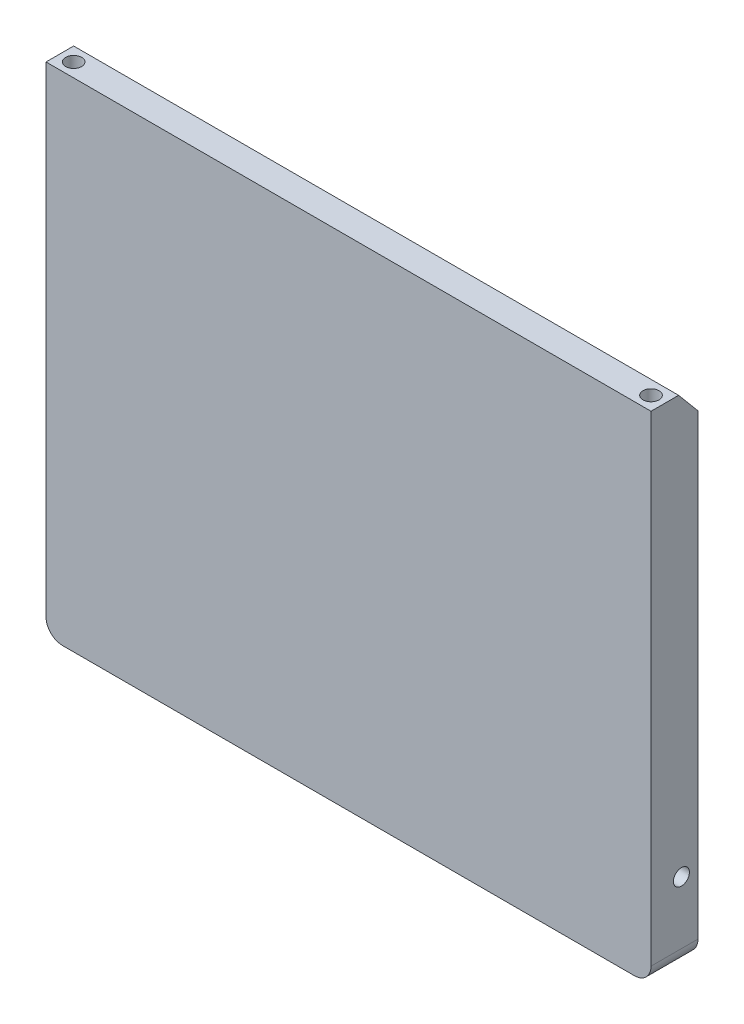
SolidWorks part; units mm, degrees
ref_plane "Front Plane" through (0, 0, 0) normal (0, 0, 1) x (1, 0, 0)
ref_plane "Top Plane" through (0, 0, 0) normal (0, 1, 0) x (1, 0, 0)
ref_plane "Right Plane" through (0, 0, 0) normal (1, 0, 0) x (0, 0, -1)
sketch "Sketch1" plane through (0, 0, 0) normal (0, 0, 1) x (1, 0, 0)
  line L1 (-5.3066, -80.8019) -> (104.2134, -80.8019)
  line L2 (-5.3066, -80.8019) -> (-5.3066, 9.1981)
  line L3 (-5.3066, 9.1981) -> (104.2134, 9.1981)
  line L4 (104.2134, -80.8019) -> (104.2134, 9.1981)
  dimension "D1" = 109.52
  dimension "D2" = 90
extrude "Boss-Extrude1" add sketch "Sketch1" along normal blind 5
sketch "Sketch2" plane through (0, 9.1981, 0) normal (0, 1, 0) x (1, 0, 0)
  line L0 (-5.3066, -5) -> (-5.3066, 0) construction
  line L1 (104.2134, -5) -> (104.2134, 0) construction
  circle A0 centre (-2.8066, -2.5) radius 1.45
  circle A1 centre (101.7134, -2.5) radius 1.45
  point P7 (-5.3066, -2.5)
  dimension "D2" = 2.9
  dimension "D4" = 2.9
  dimension "D1" = 2.5
  dimension "D3" = 2.5
extrude "Cut-Extrude1" cut sketch "Sketch2" against normal blind 7 contours A1 | A0
fillet "Fillet1" radius 3 2 edges at (104.2134, -80.8019, 2.5) (-5.3066, -80.8019, 2.5)
sketch "Sketch4" plane through (0, 0, 0) normal (0, 0, -1) x (-1, 0, 0)
  line L4 (-104.2134, 9.1981) -> (-104.2134, -77.8019)
  line L5 (-101.2134, -80.8019) -> (2.3066, -80.8019)
  line L6 (5.3066, -77.8019) -> (5.3066, 9.1981)
  line L7 (5.3066, 9.1981) -> (-104.2134, 9.1981)
  line L8 (-104.2134, 9.1981) -> (-104.2134, -77.8019)
  line L9 (-101.2134, -80.8019) -> (2.3066, -80.8019)
  line L10 (5.3066, -77.8019) -> (5.3066, 9.1981)
  line L11 (5.3066, 9.1981) -> (-104.2134, 9.1981)
  arc A2 (-104.2134, -77.8019) -> (-101.2134, -80.8019) centre (-101.2134, -77.8019) ccw
  arc A3 (2.3066, -80.8019) -> (5.3066, -77.8019) centre (2.3066, -77.8019) ccw
  arc A4 (-104.2134, -77.8019) -> (-101.2134, -80.8019) centre (-101.2134, -77.8019) ccw
  arc A5 (2.3066, -80.8019) -> (5.3066, -77.8019) centre (2.3066, -77.8019) ccw
  dimension "D1" = 0
extrude "Boss-Extrude2" add sketch "Sketch4" along normal blind 3.5
sketch "Sketch5" plane through (0, 0, -3.5) normal (0, 0, -1) x (-1, 0, 0)
  line L0 (-49.4534, 9.1981) -> (-49.4534, -80.8019) construction
  line L1 (-99.5534, 3.7981) -> (0.6466, 3.7981)
  line L2 (-99.5534, 3.7981) -> (-99.5534, -75.4019)
  line L3 (-99.5534, -75.4019) -> (0.6466, -75.4019)
  line L4 (0.6466, 3.7981) -> (0.6466, -75.4019)
  line L5 (5.3066, 9.1981) -> (-104.2134, 9.1981) construction
  line L6 (-101.2134, -80.8019) -> (2.3066, -80.8019) construction
  point P10 (-49.4534, 3.7981)
  point P11 (-99.5534, -35.8019)
  point P12 (-49.4534, -35.8019)
  dimension "D1" = 100.2
  dimension "D2" = 79.2
chamfer "Chamfer1" distance 3.5 angle 50 1 edges at (49.4534, 9.1981, -3.5)
ref_plane "Plane1" through (49.4534, 0, 0) normal (-1, 0, 0) x (0, 0, 1)
extrude "Cut-Extrude3" cut sketch "Sketch5" against normal blind 6.5
sketch "Sketch8" plane through (104.2134, 0, 0) normal (1, 0, 0) x (0, 0, -1)
  line L2 (0.5, -68.0019) -> (0.5, -65.1019) construction
  circle A2 centre (0.5, -66.5519) radius 1.45
extrude "Cut-Extrude5" cut sketch "Sketch8" against normal blind 3
mirror "Mirror2" about plane through (49.4534, 0, 0) normal (-1, 0, 0) of "Cut-Extrude5"
